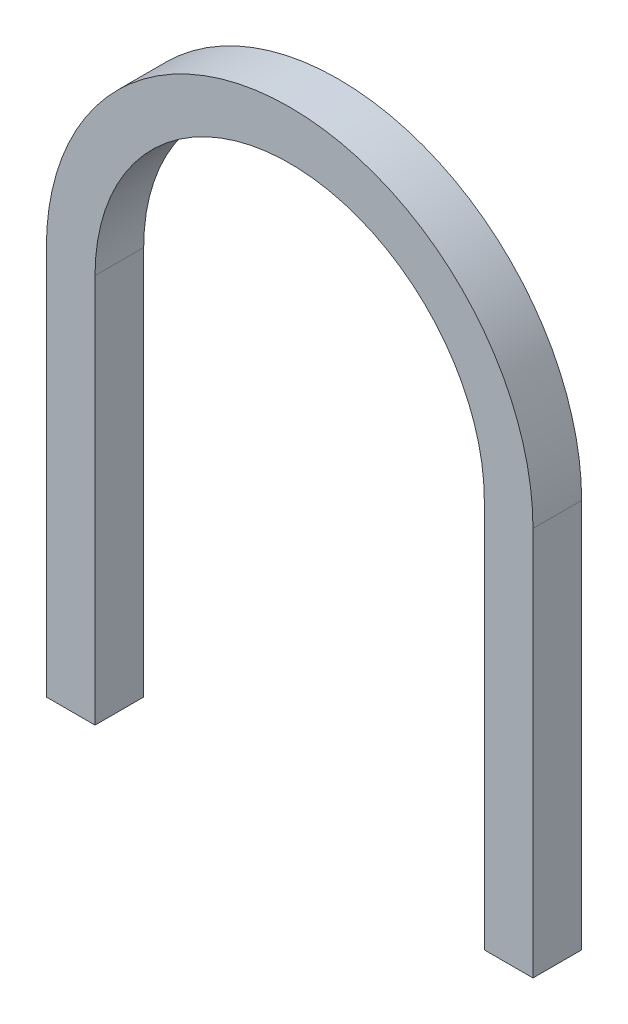
SolidWorks part; units mm, degrees
ref_plane "Plan de face" through (0, 0, 0) normal (0, 0, 1) x (1, 0, 0)
ref_plane "Plan de dessus" through (0, 0, 0) normal (0, 1, 0) x (1, 0, 0)
ref_plane "Plan de droite" through (0, 0, 0) normal (1, 0, 0) x (0, 0, -1)
sketch "Esquisse1" plane through (0, 0, 0) normal (0, 0, 1) x (1, 0, 0)
  line L0 (-20, 0) -> (-20, 40)
  line L1 (-20, 0) -> (-25, 0)
  line L2 (-25, 0) -> (-25, 40)
  line L3 (20, 40) -> (20, 0)
  line L4 (20, 0) -> (25, 0)
  line L5 (25, 0) -> (25, 40)
  line L6 (0, 0) -> (0, 36.8333) construction
  arc A0 (-20, 40) -> (20, 40) centre (0, 40) cw
  arc A1 (25, 40) -> (-25, 40) centre (0, 40) ccw
  point P15 (0, 60)
  dimension "D2" = 60
  dimension "D1" = 5
  dimension "D3" = 40
extrude "Boss.-Extru.1" add sketch "Esquisse1" along normal blind 5
